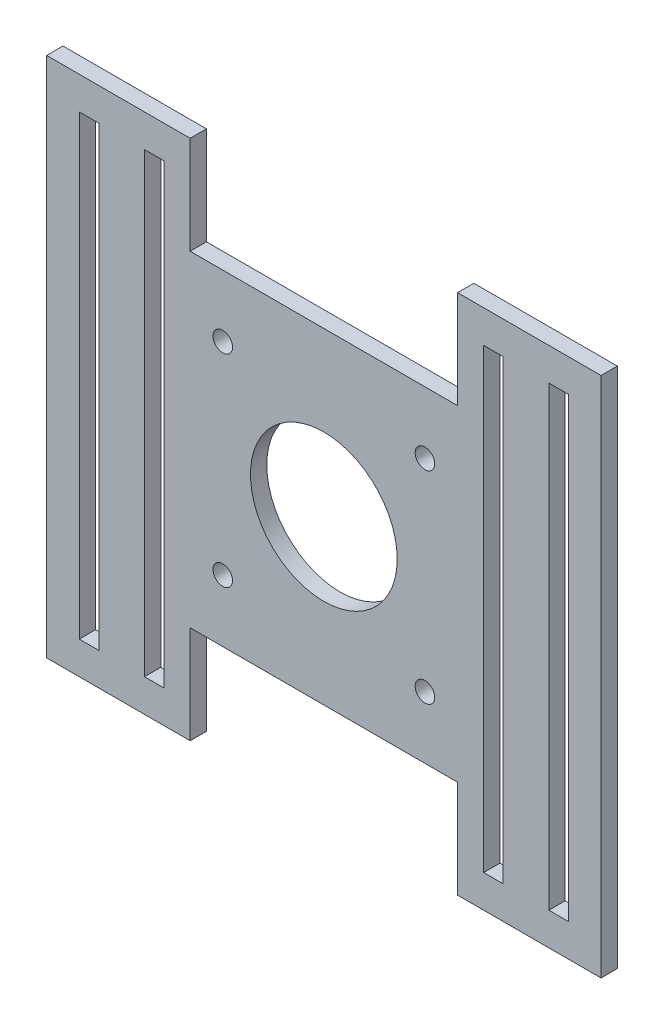
SolidWorks part; units mm, degrees
ref_plane "Front Plane" through (0, 0, 0) normal (0, 0, 1) x (1, 0, 0)
ref_plane "Top Plane" through (0, 0, 0) normal (0, 1, 0) x (1, 0, 0)
ref_plane "Right Plane" through (0, 0, 0) normal (1, 0, 0) x (0, 0, -1)
sketch "Sketch1" plane through (0, 0, 0) normal (0, 0, 1) x (1, 0, 0)
  line L1 (0, 0) -> (85, 0)
  line L2 (0, 0) -> (0, 50)
  line L3 (0, 50) -> (85, 50)
  line L4 (85, 0) -> (85, 50)
  dimension "D1" = 50
  dimension "D2" = 85
extrude "Boss-Extrude1" add sketch "Sketch1" along normal blind 2.5
sketch "Sketch5" plane through (0, 0, 0) normal (0, 0, 1) x (1, 0, 0)
  line L0 (0, -1.375) -> (0, 1.375) construction
  line L1 (0, 50) -> (22, 50)
  line L2 (0, 50) -> (0, 65)
  line L3 (0, 65) -> (22, 65)
  line L4 (22, 50) -> (22, 65)
  dimension "D1" = 22
  dimension "D2" = 15
extrude "Boss-Extrude2" add sketch "Sketch5" along normal blind 2.5
pattern_linear "LPattern4" count 2 spacing 63 along (1, 0, 0) of "Boss-Extrude2"
pattern_linear "LPattern5" count 2 spacing 65 along (0, -1, 0) of "Boss-Extrude2", "LPattern4"
sketch "Sketch2" plane through (0, 0, 2.5) normal (0, 0, 1) x (1, 0, 0)
  line L1 (5, 60) -> (8, 60)
  line L2 (5, 60) -> (5, -10)
  line L3 (5, -10) -> (8, -10)
  line L4 (8, 60) -> (8, -10)
  line L6 (0, -1.3751) -> (0, 1.3751) construction
  line L7 (0, -15) -> (22, -15) construction
  line L8 (15, -10) -> (18, -10)
  line L9 (15, -10) -> (15, 60)
  line L10 (15, 60) -> (18, 60)
  line L11 (18, -10) -> (18, 60)
  line L12 (22, 65) -> (0, 65) construction
  dimension "D1" = 3
  dimension "D2" = 5
  dimension "D3" = 5
  dimension "D4" = 5
  dimension "D5" = 3
  dimension "D6" = 7
  dimension "D7" = 5
  dimension "D8" = 5
extrude "Cut-Extrude1" cut sketch "Sketch2" against normal blind 2.5
pattern_linear "LPattern1" count 2 spacing 62 along (1, 0, 0) of "Cut-Extrude1"
sketch "Sketch3" plane through (0, 0, 2.5) normal (0, 0, 1) x (1, 0, 0)
  line L0 (85, -15) -> (85, 65) construction
  line L1 (0, -1.3751) -> (0, 1.3751) construction
  line L3 (63, 50) -> (22, 50) construction
  line L4 (1.3751, 0) -> (-1.3751, 0) construction
  circle A0 centre (42.5, 25) radius 11.25
  dimension "D5" = 22.5
  dimension "D1" = 42.5
  dimension "D2" = 42.5
  dimension "D3" = 25
  dimension "D4" = 25
extrude "Cut-Extrude2" cut sketch "Sketch3" against normal through all
sketch "Sketch4" plane through (0, 0, 2.5) normal (0, 0, 1) x (1, 0, 0)
  circle A0 centre (27, 40.5) radius 1.5
  circle A1 centre (42.5, 25) radius 11.25 construction
  dimension "D1" = 15.5
  dimension "D2" = 3
  dimension "D3" = 15.5
extrude "Cut-Extrude3" cut sketch "Sketch4" against normal through all
pattern_linear "LPattern2" count 2 spacing 31 along (0, -1, 0) of "Cut-Extrude3"
pattern_linear "LPattern3" count 2 spacing 31 along (1, 0, 0) of "Cut-Extrude3", "LPattern2"
